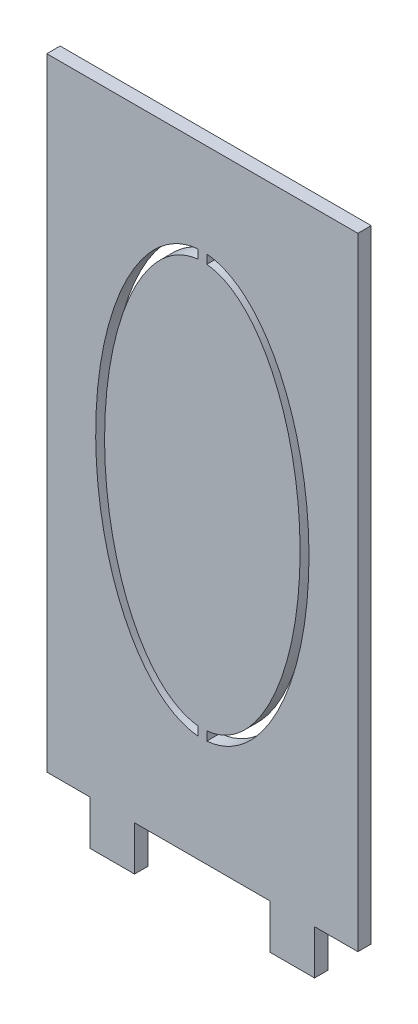
SolidWorks part; units mm, degrees
material "Glas"
ref_plane "Ebene vorne" through (0, 0, 0) normal (0, 0, 1) x (1, 0, 0)
ref_plane "Ebene oben" through (0, 0, 0) normal (0, 1, 0) x (1, 0, 0)
ref_plane "Ebene rechts" through (0, 0, 0) normal (1, 0, 0) x (0, 0, -1)
sketch "Skizze1" plane through (0, 0, 0) normal (0, 0, 1) x (1, 0, 0)
  line L1 (0, 0) -> (35, 0)
  line L2 (0, 0) -> (0, 75)
  line L3 (0, 75) -> (35, 75)
  line L4 (35, 0) -> (35, 75)
  dimension "D1" = 35
  dimension "D2" = 75
extrude "Aufsatz-Linear austragen1" add sketch "Skizze1" along normal blind 1.5
sketch "Skizze3" plane through (0, 0, 1.5) normal (0, 0, 1) x (1, 0, 0)
  line L0 (0, 0) -> (35, 0) construction
  line L1 (9.875, 0) -> (25.125, 0)
  line L2 (9.875, 0) -> (9.875, 5)
  line L3 (9.875, 5) -> (25.125, 5)
  line L4 (25.125, 0) -> (25.125, 5)
  line L5 (35, 0) -> (35, 75) construction
  line L6 (30.125, 5) -> (35, 5)
  line L7 (30.125, 5) -> (30.125, 0)
  line L8 (30.125, 0) -> (35, 0)
  line L9 (35, 5) -> (35, 0)
  line L10 (4.875, 5) -> (0, 5)
  line L11 (4.875, 5) -> (4.875, 0)
  line L12 (4.875, 0) -> (0, 0)
  line L13 (0, 5) -> (0, 0)
  dimension "D1" = 4.875
  dimension "D2" = 4.875
  dimension "D3" = 0
  dimension "D4" = 5
  dimension "D5" = 5
  dimension "D6" = 5
  dimension "D7" = 5
extrude "Schnitt-Linear austragen12" cut sketch "Skizze3" against normal blind 20
sketch "Skizze4" plane through (0, 0, 1.5) normal (0, 0, 1) x (1, 0, 0)
  line L2 (35, 75) -> (0, 75) construction
  ellipse E0 centre (17.5, 40.75) end of major axis (17.5, 64.5) minor radius 12
  ellipse E1 centre (17.5, 40.75) end of major axis (17.5, 63.5) minor radius 11
  point P1 (0, 0)
  dimension "D1" = 22.75
  dimension "D2" = 23.75
  dimension "D6" = 10.5
extrude "Schnitt-Linear austragen13" cut sketch "Skizze4" against normal blind 20
sketch "Skizze6" plane through (0, 0, 1.5) normal (0, 0, 1) x (1, 0, 0)
  line L0 (35, 5) -> (35, 75) construction
  line L1 (17, 65.8133) -> (18, 65.8133)
  line L2 (17, 65.8133) -> (17, 13.013)
  line L3 (17, 13.013) -> (18, 13.013)
  line L4 (18, 65.8133) -> (18, 13.013)
  dimension "D1" = 1
  dimension "D2" = 17
extrude "Aufsatz-Linear austragen4" add sketch "Skizze6" against normal blind 1.5
